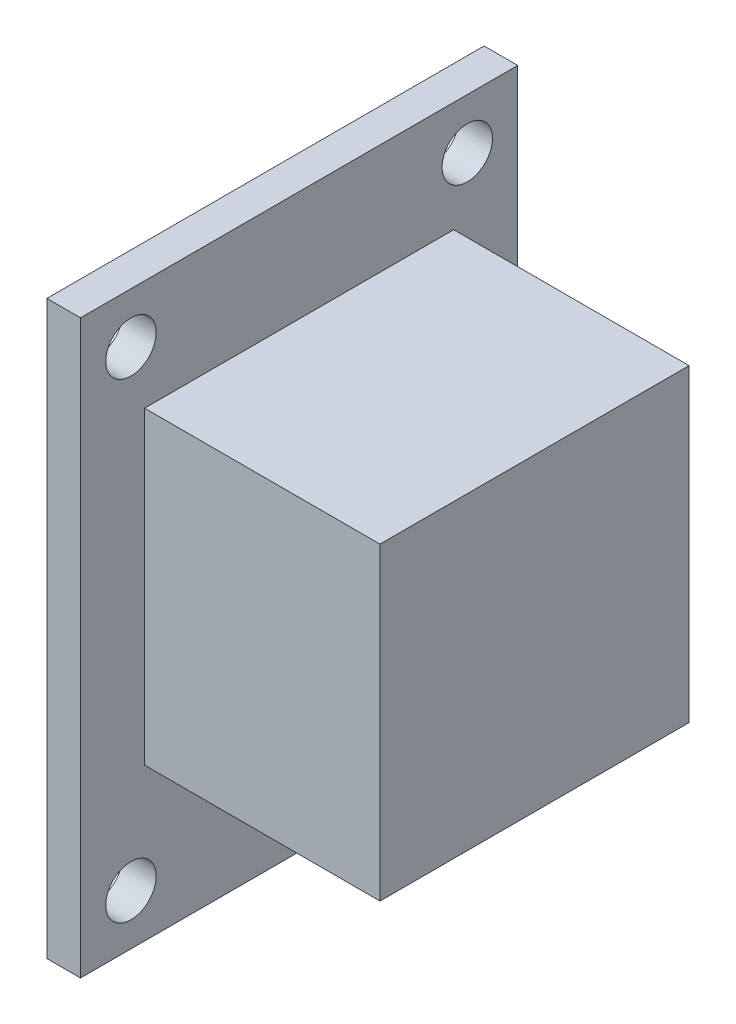
SolidWorks part; units mm, degrees
ref_plane "前视基准面" through (0, 0, 0) normal (0, 0, 1) x (1, 0, 0)
ref_plane "上视基准面" through (0, 0, 0) normal (0, 1, 0) x (1, 0, 0)
ref_plane "右视基准面" through (0, 0, 0) normal (1, 0, 0) x (0, 0, -1)
other "Configuration Table"
sketch "草图1" plane through (0, 0, 0) normal (1, 0, 0) x (0, 0, -1)
  line L1 (-17.25, -13.25) -> (17.25, -13.25) construction
  line L2 (-17.25, -13.25) -> (-17.25, 13.25) construction
  line L3 (-17.25, 13.25) -> (17.25, 13.25) construction
  line L4 (17.25, -13.25) -> (17.25, 13.25) construction
  line L5 (-17.25, -13.25) -> (17.25, 13.25) construction
  line L6 (-17.25, 13.25) -> (17.25, -13.25) construction
  line L7 (-9.1924, -7.9424) -> (9.1924, -7.9424)
  line L8 (-9.1924, -7.9424) -> (-9.1924, 10.4424)
  line L9 (-9.1924, 10.4424) -> (9.1924, 10.4424)
  line L10 (9.1924, -7.9424) -> (9.1924, 10.4424)
  line L11 (-9.1924, -7.9424) -> (9.1924, 10.4424) construction
  line L12 (-9.1924, 10.4424) -> (9.1924, -7.9424) construction
  circle A0 centre (0, 1.25) radius 13 construction
  point P0 (0, 0)
  dimension "D3" = 26
  dimension "D1" = 34.5
  dimension "D2" = 26.5
  dimension "D4" = 17.25
  dimension "D5" = 17.25
  dimension "D6" = 12
  dimension "D7" = 90
extrude "凸台-拉伸2" add sketch "草图1" along normal blind 14
sketch "草图5" plane through (0, 0, 0) normal (-1, 0, 0) x (0, 0, 1)
  line L1 (-13, -17) -> (13, -17)
  line L2 (-13, -17) -> (-13, 17)
  line L3 (-13, 17) -> (13, 17)
  line L4 (-9.1924, 10.4424) -> (-9.1924, -7.9424)
  line L5 (-9.1924, -7.9424) -> (9.1924, -7.9424)
  line L6 (9.1924, -7.9424) -> (9.1924, 10.4424)
  line L7 (9.1924, 10.4424) -> (-9.1924, 10.4424)
  line L8 (-9.1924, 10.4424) -> (-9.1924, -7.9424) construction
  line L9 (-9.1924, -7.9424) -> (9.1924, -7.9424) construction
  line L10 (9.1924, -7.9424) -> (9.1924, 10.4424) construction
  line L11 (9.1924, 10.4424) -> (-9.1924, 10.4424) construction
  line L12 (13, -17) -> (13, 17)
  line L13 (-13, -17) -> (13, 17) construction
  line L14 (-13, 17) -> (13, -17) construction
  point P2 (0, 0)
  dimension "D2" = 34
  dimension "D3" = 26
  dimension "D1" = 0
extrude "凸台-拉伸4" add sketch "草图5" along normal blind 2
sketch "草图6" plane through (0, 0, 0) normal (1, 0, 0) x (0, 0, -1)
  line L0 (-13, 17) -> (13, 17) construction
  line L1 (-13, -17) -> (-13, 17) construction
  line L2 (13, 17) -> (13, -17) construction
  line L3 (13, -17) -> (-13, -17) construction
  circle A0 centre (-10, 14) radius 1.5
  circle A1 centre (10, 14) radius 1.5
  circle A2 centre (-10, -14) radius 1.5
  circle A3 centre (10, -14) radius 1.5
  point P12 (-16.4018, 14.7113)
  point P17 (0, 0)
  point P18 (0, 0)
  dimension "D1" = 3
  dimension "D2" = 3
  dimension "D3" = 3
  dimension "D4" = 3
  dimension "D5" = 3
  dimension "D6" = 3
  dimension "D7" = 3
  dimension "D8" = 3
  dimension "D9" = 3
  dimension "D10" = 3
  dimension "D11" = 3
  dimension "D12" = 3
extrude "切除-拉伸1" cut sketch "草图6" against normal blind 2
